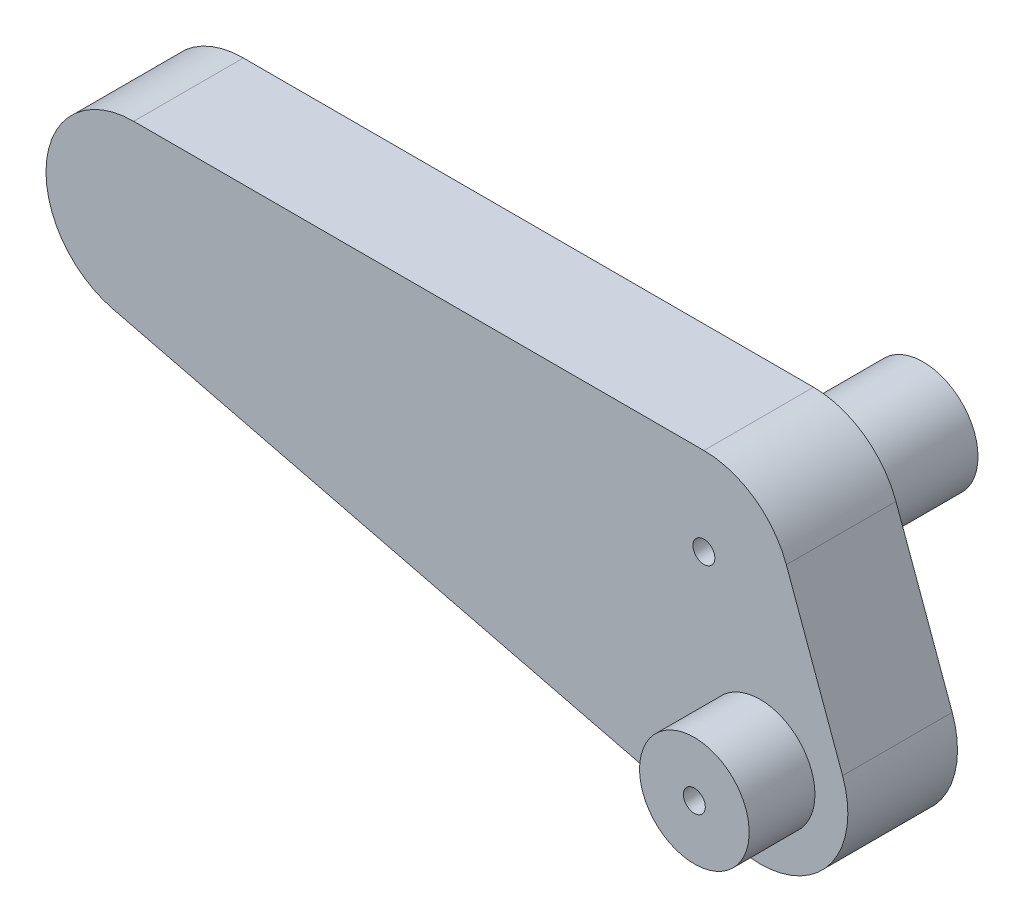
SolidWorks part; units mm, degrees
material "ABS"
ref_plane "Front Plane" through (0, 0, 0) normal (0, 0, 1) x (1, 0, 0)
ref_plane "Top Plane" through (0, 0, 0) normal (0, 1, 0) x (1, 0, 0)
ref_plane "Right Plane" through (0, 0, 0) normal (1, 0, 0) x (0, 0, -1)
sketch "Sketch1" plane through (0, 0, 0) normal (0, 0, 1) x (1, 0, 0)
  line L0 (0, 0) -> (-26, 0)
  line L1 (0, 0) -> (2.5652, -7.0477)
  dimension "D1" = 26
  dimension "D2" = 7.5
  dimension "D3" = 110
sketch "Sketch2" plane through (0, 0, 0) normal (0, 0, 1) x (1, 0, 0)
  line L0 (-26, 4) -> (0, 4)
  line L1 (3.7588, 1.3681) -> (6.3239, -5.6796)
  line L2 (1.607, -10.9312) -> (-26.9582, -3.8835)
  circle A0 centre (-26, 0) radius 2.5
  arc A1 (-26, 4) -> (-26.9582, -3.8835) centre (-26, 0) ccw
  circle A2 centre (0, 0) radius 2.5
  arc A3 (3.7588, 1.3681) -> (0, 4) centre (0, 0) ccw
  circle A4 centre (2.5652, -7.0477) radius 2.5
  arc A5 (1.607, -10.9312) -> (6.3239, -5.6796) centre (2.5652, -7.0477) ccw
  dimension "D1" = 5
  dimension "D2" = 8
  dimension "D3" = 5
  dimension "D4" = 8
  dimension "D5" = 5
  dimension "D6" = 8
extrude "Boss-Extrude1" add sketch "Sketch2" along normal blind 5
sketch "Sketch3" plane through (0, 0, 5) normal (0, 0, 1) x (1, 0, 0)
  circle A0 centre (0, 0) radius 2.5
  circle A1 centre (0, 0) radius 0.5
  dimension "D1" = 5
  dimension "D2" = 1
extrude "Boss-Extrude2" add sketch "Sketch3" against normal blind 10
sketch "Sketch4" plane through (0, 0, 0) normal (0, 0, -1) x (-1, 0, 0)
  circle A0 centre (-2.5652, -7.0477) radius 2.5
  circle A1 centre (-2.5652, -7.0477) radius 0.5
  dimension "D1" = 1
  dimension "D2" = 5
extrude "Boss-Extrude3" add sketch "Sketch4" against normal blind 8
sketch "Sketch5" plane through (0, 0, 0) normal (0, 0, -1) x (-1, 0, 0)
  circle A0 centre (26, 0) radius 2.5
  dimension "D1" = 5
extrude "Boss-Extrude4" add sketch "Sketch5" against normal blind 5
